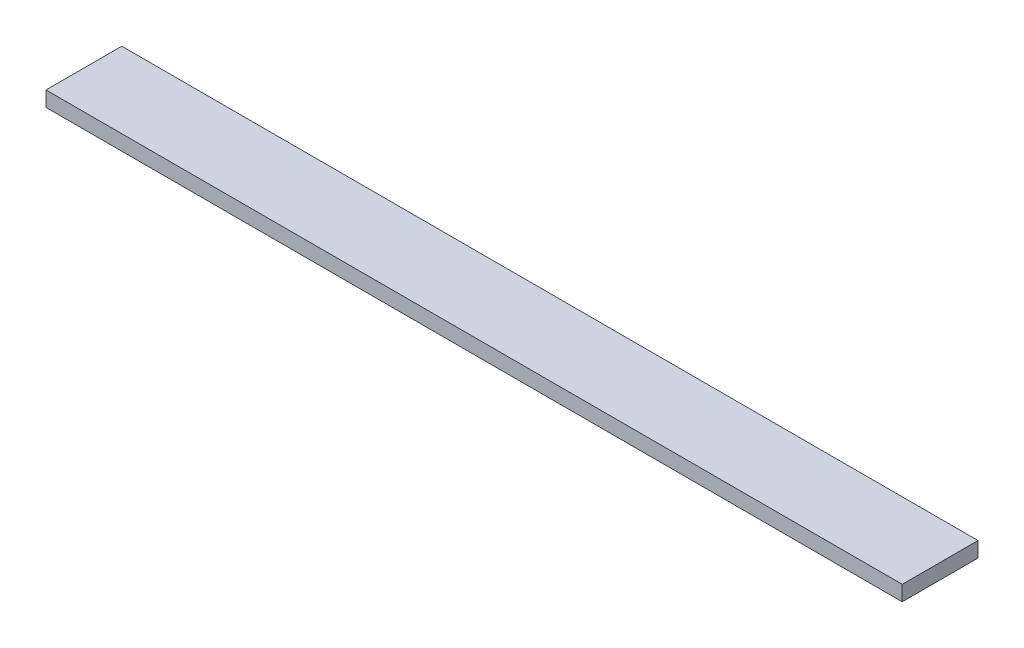
SolidWorks part; units mm, degrees
ref_plane "Front Plane" through (0, 0, 0) normal (0, 0, 1) x (1, 0, 0)
ref_plane "Top Plane" through (0, 0, 0) normal (0, 1, 0) x (1, 0, 0)
ref_plane "Right Plane" through (0, 0, 0) normal (1, 0, 0) x (0, 0, -1)
sketch "Sketch1" plane through (0, 0, 0) normal (0, 1, 0) x (1, 0, 0)
  line L1 (0, 0) -> (113, 0)
  line L2 (0, 0) -> (0, 10)
  line L3 (0, 10) -> (113, 10)
  line L4 (113, 0) -> (113, 10)
  dimension "D1" = 113
  dimension "D2" = 10
extrude "Boss-Extrude1" add sketch "Sketch1" along normal blind 2
